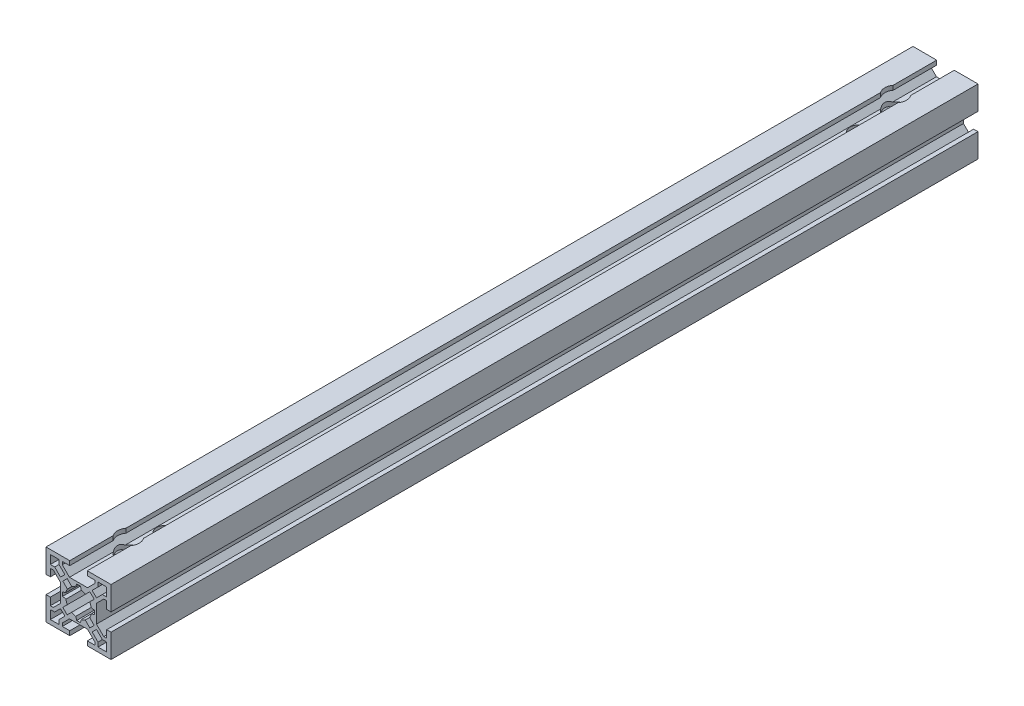
SolidWorks part; units mm, degrees
material "Liga 1060"
ref_plane "Plano frontal" through (0, 0, 0) normal (0, 0, 1) x (1, 0, 0)
ref_plane "Plano superior" through (0, 0, 0) normal (0, 1, 0) x (1, 0, 0)
ref_plane "Plano direito" through (0, 0, 0) normal (1, 0, 0) x (0, 0, -1)
ref_plane "Plano1" through (0, 0, 100) normal (0, 0, 1) x (1, 0, 0)
sketch "Esboço1" plane through (0, 0, 0) normal (0, 0, 1) x (1, 0, 0)
  line L0 (0, 0) -> (-15, -15) construction
  line L1 (-13, -4.05) -> (-15, -4.05)
  line L2 (-11.6273, -7.5) -> (-8.3, -4.1727)
  line L3 (-15, -15) -> (-4.05, -15)
  line L4 (-11.6273, -7.5) -> (-13, -7.5)
  line L5 (-7.5, -13) -> (-4.05, -13)
  line L6 (-7.2393, -5.2334) -> (-5.1254, -3.1194)
  line L7 (-8.3, -4.1727) -> (-8.3, 4.1727)
  line L8 (-11.006, -9) -> (-13, -9)
  line L9 (-13, -13) -> (-9, -13)
  line L10 (-13, -13) -> (-13, -9)
  line L11 (-13, -7.5) -> (-13, -4.05)
  line L12 (-15, -15) -> (-15, -4.05)
  line L13 (0, 0) -> (0, -8.3) construction
  line L14 (0, 0) -> (-8.3, 0) construction
  line L15 (7.2393, -5.2334) -> (5.2334, -7.2393)
  line L16 (4.05, -13) -> (4.05, -15)
  line L17 (-9, -11.006) -> (-9, -13)
  line L18 (0, 0) -> (0, 7.3) construction
  line L19 (7.5, -11.6273) -> (4.1727, -8.3)
  line L20 (7.5, -11.6273) -> (7.5, -13)
  line L21 (5.2334, -7.2393) -> (3.1194, -5.1254)
  line L22 (9, -11.006) -> (9, -13)
  line L23 (15, -15) -> (15, -4.05)
  line L24 (13, -7.5) -> (13, -4.05)
  line L25 (13, -13) -> (13, -9)
  line L26 (13, -13) -> (9, -13)
  line L27 (11.006, -9) -> (13, -9)
  line L28 (-4.1727, -8.3) -> (4.1727, -8.3)
  line L29 (8.3, -4.1727) -> (8.3, 4.1727)
  line L30 (7.2393, -5.2334) -> (5.1254, -3.1194)
  line L31 (7.5, -13) -> (4.05, -13)
  line L32 (11.6273, -7.5) -> (13, -7.5)
  line L33 (15, -15) -> (4.05, -15)
  line L34 (11.6273, -7.5) -> (8.3, -4.1727)
  line L35 (13, -4.05) -> (15, -4.05)
  line L36 (-7.2393, 5.2334) -> (-5.2334, 7.2393)
  line L37 (-4.05, 13) -> (-4.05, 15)
  line L38 (-7.5, 11.6273) -> (-4.1727, 8.3)
  line L39 (-7.5, 11.6273) -> (-7.5, 13)
  line L40 (-5.2334, 7.2393) -> (-3.1194, 5.1254)
  line L41 (13, 4.05) -> (15, 4.05)
  line L42 (11.6273, 7.5) -> (8.3, 4.1727)
  line L43 (15, 15) -> (4.05, 15)
  line L44 (11.6273, 7.5) -> (13, 7.5)
  line L45 (7.5, 13) -> (4.05, 13)
  line L46 (7.2393, 5.2334) -> (5.1254, 3.1194)
  line L47 (-5.2334, -7.2393) -> (-3.1194, -5.1254)
  line L48 (-4.1727, 8.3) -> (4.1727, 8.3)
  line L49 (11.006, 9) -> (13, 9)
  line L50 (13, 13) -> (9, 13)
  line L51 (13, 13) -> (13, 9)
  line L52 (13, 7.5) -> (13, 4.05)
  line L53 (15, 15) -> (15, 4.05)
  line L54 (9, 11.006) -> (9, 13)
  line L55 (5.2334, 7.2393) -> (3.1194, 5.1254)
  line L56 (-7.5, -11.6273) -> (-7.5, -13)
  line L57 (7.5, 11.6273) -> (7.5, 13)
  line L58 (7.5, 11.6273) -> (4.1727, 8.3)
  line L59 (-9, 11.006) -> (-9, 13)
  line L60 (-7.5, -11.6273) -> (-4.1727, -8.3)
  line L61 (4.05, 13) -> (4.05, 15)
  line L62 (7.2393, 5.2334) -> (5.2334, 7.2393)
  line L63 (-15, 15) -> (-15, 4.05)
  line L64 (-13, 7.5) -> (-13, 4.05)
  line L65 (-13, 13) -> (-13, 9)
  line L66 (-13, 13) -> (-9, 13)
  line L67 (-11.006, 9) -> (-13, 9)
  line L68 (-7.2393, 5.2334) -> (-5.1254, 3.1194)
  line L69 (-4.05, -13) -> (-4.05, -15)
  line L70 (-7.5, 13) -> (-4.05, 13)
  line L71 (-11.6273, 7.5) -> (-13, 7.5)
  line L72 (-15, 15) -> (-4.05, 15)
  line L73 (-11.6273, 7.5) -> (-8.3, 4.1727)
  line L74 (-13, 4.05) -> (-15, 4.05)
  line L75 (-6.294, -8.3) -> (-8.3, -6.294)
  line L76 (-6.294, -8.3) -> (-9, -11.006)
  line L77 (-8.3, -6.294) -> (-11.006, -9)
  line L78 (-8.3, 6.294) -> (-11.006, 9)
  line L79 (-6.294, 8.3) -> (-8.3, 6.294)
  line L80 (-6.294, 8.3) -> (-9, 11.006)
  line L81 (6.294, 8.3) -> (9, 11.006)
  line L82 (6.294, 8.3) -> (8.3, 6.294)
  line L83 (8.3, 6.294) -> (11.006, 9)
  line L84 (6.294, -8.3) -> (9, -11.006)
  line L85 (6.294, -8.3) -> (8.3, -6.294)
  line L86 (8.3, -6.294) -> (11.006, -9)
  line L87 (5.8582, -1.2966) -> (7.3, -0.8598)
  line L88 (7.3, -0.8598) -> (7.3, 0.8598)
  line L89 (5.8582, 1.2966) -> (7.3, 0.8598)
  line L90 (-1.2966, -5.8582) -> (-0.8598, -7.3)
  line L91 (-0.8598, -7.3) -> (0.8598, -7.3)
  line L92 (1.2966, -5.8582) -> (0.8598, -7.3)
  line L93 (1.2966, 5.8582) -> (0.8598, 7.3)
  line L94 (0.8598, 7.3) -> (-0.8598, 7.3)
  line L95 (-1.2966, 5.8582) -> (-0.8598, 7.3)
  line L96 (-5.8582, 1.2966) -> (-7.3, 0.8598)
  line L97 (-7.3, 0.8598) -> (-7.3, -0.8598)
  line L98 (-5.8582, -1.2966) -> (-7.3, -0.8598)
  line L99 (-7.2393, -5.2334) -> (-5.2334, -7.2393)
  arc A0 (-5.1254, -3.1194) -> (-5.8582, -1.2966) centre (0, 0) cw
  arc A1 (5.1254, -3.1194) -> (5.8582, -1.2966) centre (0, 0) ccw
  arc A2 (-3.1194, 5.1254) -> (-1.2966, 5.8582) centre (0, 0) cw
  arc A3 (-3.1194, -5.1254) -> (-1.2966, -5.8582) centre (0, 0) ccw
  arc A4 (1.2966, -5.8582) -> (3.1194, -5.1254) centre (0, 0) ccw
  arc A5 (5.8582, 1.2966) -> (5.1254, 3.1194) centre (0, 0) ccw
  arc A6 (1.2966, 5.8582) -> (3.1194, 5.1254) centre (0, 0) cw
  arc A7 (-5.8582, 1.2966) -> (-5.1254, 3.1194) centre (0, 0) cw
  point P4 (6.2364, 6.2364)
  point P6 (-6.2364, -6.2364)
  point P17 (6.2364, -6.2364)
  point P41 (-6.2364, 6.2364)
  point P60 (8.3, 0)
  point P85 (-7.297, -7.297)
  point P109 (0, 7.3)
  point P111 (7.3, 0)
  point P112 (0, 0)
  point P115 (0, -7.3)
  point P118 (-7.3, 0)
  point P119 (0, 0)
  dimension "D2" = 6
  dimension "D1" = 2
  dimension "D3" = 5.8368
  dimension "D4" = 1.5
  dimension "D5" = 1.5
  dimension "D6" = 1
  dimension "D7" = 1.7196
  dimension "D8" = 2.5933
  dimension "D9" = 30
  dimension "D10" = 8.1
  dimension "D11" = 15
extrude "Ressalto-extrusão1" add sketch "Esboço1" against normal mid plane 400
sketch "Esboço2" plane through (0, 0, 0) normal (0, 1, 0) x (1, 0, 0)
  line L0 (0, 160) -> (0, -160) construction
  line L1 (0, 0) -> (49.5999, 0) construction
  line L2 (0, -160) -> (0, -177) construction
  circle A0 centre (0, -160) radius 4
  circle A1 centre (0, 160) radius 4
  circle A2 centre (0, -177) radius 5
  circle A3 centre (0, 177) radius 5
  dimension "D1" = 8
  dimension "D2" = 40
  dimension "D3" = 10
  dimension "D4" = 17
extrude "Corte-extrusão1" cut sketch "Esboço2" against normal through all and the other way through all
sketch "Esboço3" plane through (0, 15, 0) normal (0, 1, 0) x (1, 0, 0)
  circle A0 centre (0, 177) radius 9.5
  dimension "D1" = 19
extrude "Corte-extrusão2" [suppressed] cut sketch "Esboço3" against normal blind 1
mirror "Espelhar1" [suppressed] about plane through (0, 0, 0) normal (0, 0, 1)
mirror "Espelhar2" [suppressed] about plane through (0, 0, 0) normal (0, 1, 0)
